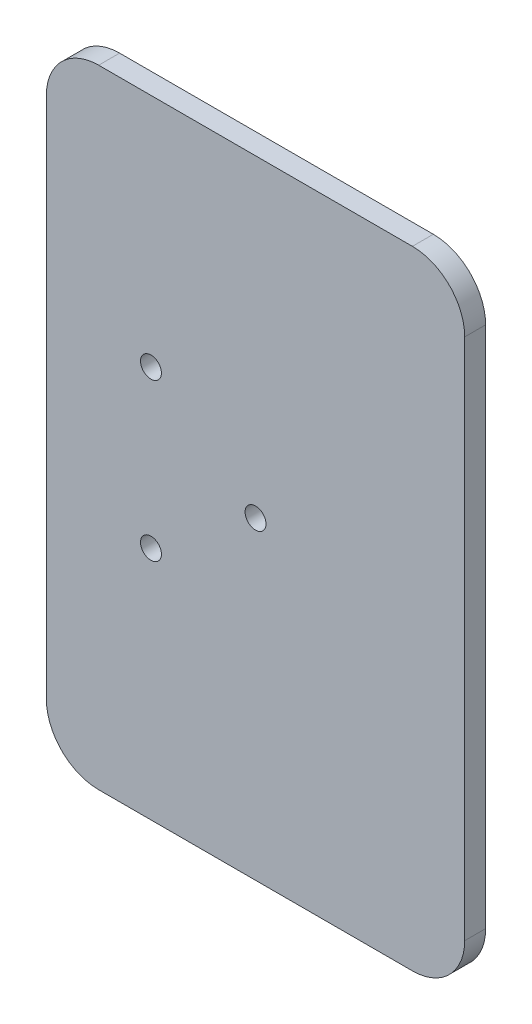
SolidWorks part; units mm, degrees
ref_plane "Front Plane" through (0, 0, 0) normal (0, 0, 1) x (1, 0, 0)
ref_plane "Top Plane" through (0, 0, 0) normal (0, 1, 0) x (1, 0, 0)
ref_plane "Right Plane" through (0, 0, 0) normal (1, 0, 0) x (0, 0, -1)
sketch "Sketch1" plane through (0, 0, 0) normal (0, 0, 1) x (1, 0, 0)
  line L1 (-65.9851, 26.8064) -> (-25.9851, 26.8064)
  line L2 (-65.9851, 26.8064) -> (-65.9851, -33.1936)
  line L3 (-65.9851, -33.1936) -> (-25.9851, -33.1936)
  line L4 (-25.9851, 26.8064) -> (-25.9851, -33.1936)
  dimension "D1" = 40
  dimension "D2" = 60
extrude "Boss-Extrude4" add sketch "Sketch1" against normal blind 2 contours L2 L3 L4 L1
fillet "Fillet1" radius 5 4 edges at (-25.9851, 26.8064, -1) (-25.9851, -33.1936, -1) (-65.9851, -33.1936, -1) (-65.9851, 26.8064, -1)
sketch "Sketch12" plane through (0, 0, -2) normal (0, 0, -1) x (-1, 0, 0)
  line L0 (65.9851, 21.8064) -> (65.9851, -28.1936) construction
  line L1 (60.9851, 26.8064) -> (30.9851, 26.8064) construction
  circle A0 centre (45.9851, -3.1936) radius 1
  dimension "D1" = 2
  dimension "D2" = 20
  dimension "D3" = 30
extrude "Cut-Extrude6" cut sketch "Sketch12" against normal blind 12 contours A0
sketch "Sketch13" plane through (0, 0, -2) normal (0, 0, -1) x (-1, 0, 0)
  line L0 (65.9851, 21.8064) -> (65.9851, -28.1936) construction
  line L1 (60.9851, 26.8064) -> (30.9851, 26.8064) construction
  line L2 (60.9851, -33.1936) -> (30.9851, -33.1936) construction
  circle A0 centre (55.9851, 4.3064) radius 1
  circle A1 centre (55.9851, -10.6936) radius 1
  dimension "D1" = 10
  dimension "D2" = 22.5
  dimension "D3" = 22.5
  dimension "D4" = 10
extrude "Cut-Extrude7" cut sketch "Sketch13" against normal blind 10 and the other way blind 8
